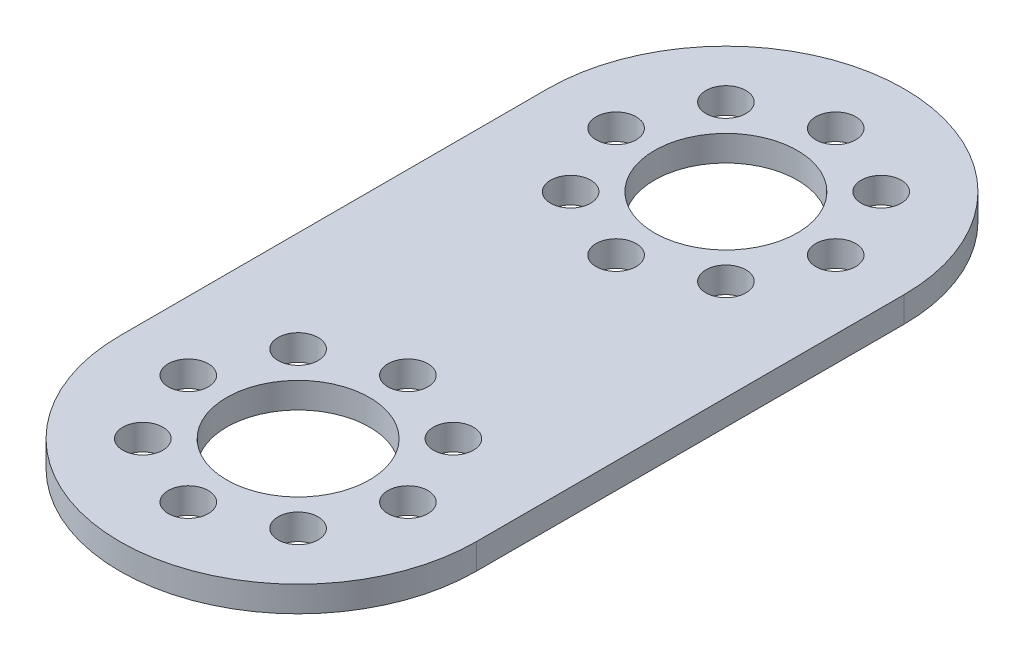
SolidWorks part; units mm, degrees
ref_plane "Front Plane" through (0, 0, 0) normal (0, 0, 1) x (1, 0, 0)
ref_plane "Top Plane" through (0, 0, 0) normal (0, 1, 0) x (1, 0, 0)
ref_plane "Right Plane" through (0, 0, 0) normal (1, 0, 0) x (0, 0, -1)
ref_plane "Plane1" through (0, 0, 0) normal (0, -1, 0) x (1, 0, 0)
sketch "Sketch1" plane through (0, 0, 0) normal (0, -1, 0) x (1, 0, 0)
  line L0 (15.875, -19.05) -> (15.875, 19.05)
  line L1 (-15.875, 19.05) -> (-15.875, -19.05)
  arc A0 (15.875, 19.05) -> (-15.875, 19.05) centre (0, 19.05) ccw
  arc A1 (-15.875, -19.05) -> (15.875, -19.05) centre (0, -19.05) ccw
  circle A2 centre (0, -19.05) radius 6.3627
  circle A3 centre (0, 19.05) radius 6.3627
  circle A4 centre (9.779, 19.05) radius 1.7844
  circle A5 centre (6.9148, 12.1352) radius 1.7844
  circle A6 centre (0, 9.271) radius 1.7844
  circle A7 centre (-6.9148, 12.1352) radius 1.7844
  circle A8 centre (-9.779, 19.05) radius 1.7844
  circle A9 centre (-6.9148, 25.9648) radius 1.7844
  circle A10 centre (0, 28.829) radius 1.7844
  circle A11 centre (6.9148, 25.9648) radius 1.7844
  circle A12 centre (9.779, -19.05) radius 1.7844
  circle A13 centre (6.9148, -12.1352) radius 1.7844
  circle A14 centre (0, -9.271) radius 1.7843
  circle A15 centre (-6.9148, -12.1352) radius 1.7844
  circle A16 centre (-9.779, -19.05) radius 1.7844
  circle A17 centre (-6.9148, -25.9648) radius 1.7844
  circle A18 centre (0, -28.829) radius 1.7844
  circle A19 centre (6.9148, -25.9648) radius 1.7844
extrude "Boss-Extrude1" add sketch "Sketch1" against normal blind 2.286
